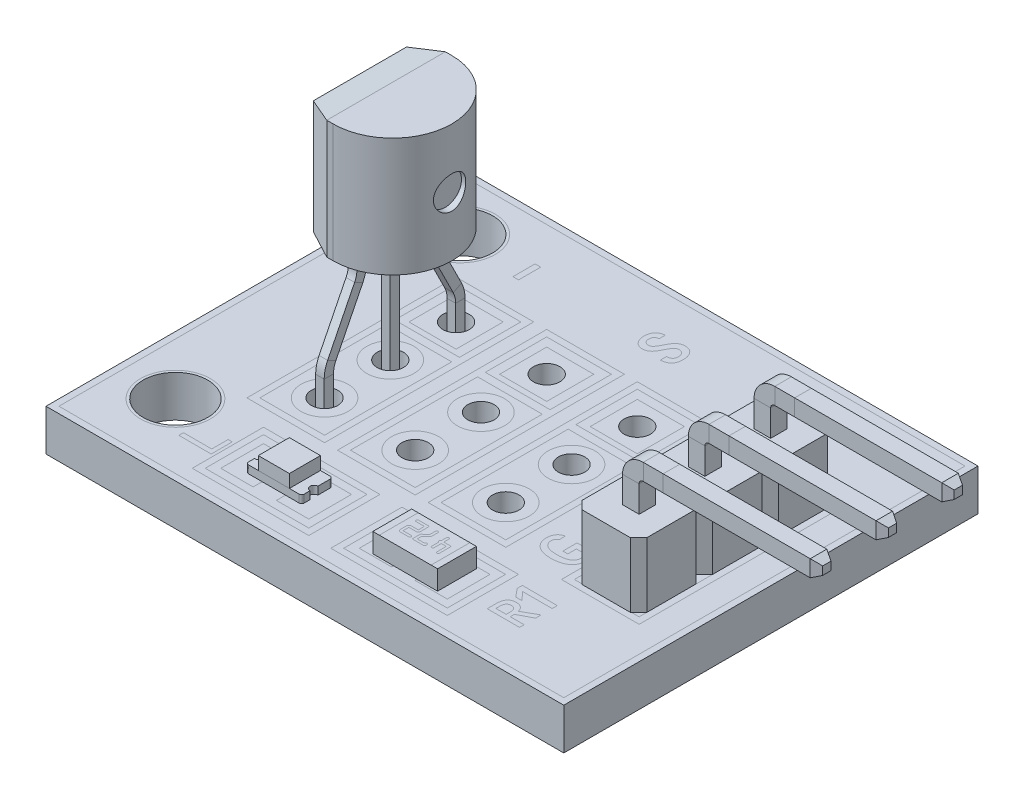
SolidWorks part; units mm, degrees
ref_plane "Front Plane" through (0, 0, 0) normal (0, 0, 1) x (1, 0, 0)
ref_plane "Top Plane" through (0, 0, 0) normal (0, 1, 0) x (1, 0, 0)
ref_plane "Right Plane" through (0, 0, 0) normal (1, 0, 0) x (0, 0, -1)
sketch "Sketch2" plane through (0, 0, 0) normal (0, 1, 0) x (1, 0, 0)
  line L0 (7.25, -2.34) -> (7.25, 2.74) construction
  line L5 (10, 8) -> (-10, 8)
  line L6 (10, 8) -> (10, -8)
  line L7 (10, -8) -> (-10, -8)
  line L8 (-10, 8) -> (-10, -8)
  circle A0 centre (-7.75, -5.25) radius 1.25
  circle A1 centre (-7.75, 5.75) radius 1.25
  circle A2 centre (2.1, 0.2) radius 0.51
  circle A3 centre (2.1, 2.74) radius 0.51
  circle A4 centre (2.1, -2.34) radius 0.51
  circle A5 centre (-1.4, -2.34) radius 0.51
  circle A6 centre (-1.4, 0.2) radius 0.51
  circle A7 centre (-1.4, 2.74) radius 0.51
  circle A8 centre (-4.9, -2.34) radius 0.51
  circle A9 centre (-4.9, 0.2) radius 0.51
  circle A10 centre (-4.9, 2.74) radius 0.51
  circle A11 centre (7.25, 0.2) radius 0.51
  circle A12 centre (7.25, 2.74) radius 0.51
  circle A13 centre (7.25, -2.34) radius 0.51
  point P35 (10, 0)
  point P37 (0, 8)
  dimension "D1" = 2.5
  dimension "D4" = 2.25
  dimension "D5" = 2.75
  dimension "D6" = 1.02
  dimension "D7" = 8.2
  dimension "D8" = 7.9
  dimension "D10" = 2.54
  dimension "D11" = 2.54
  dimension "D12" = 1.02
  dimension "D13" = 2.75
  dimension "D2" = 16
  dimension "D3" = 20
  dimension "D9" = 2.25
  dimension "D14" = 3
extrude "Boss-Extrude1" add sketch "Sketch2" along normal blind 1.6
sketch "Sketch3" plane through (0, 1.6, 0) normal (0, 1, 0) x (1, 0, 0)
  line L0 (-6.15, 3.99) -> (-3.65, 3.99)
  line L1 (-5.81, 1.83) -> (-3.99, 1.83)
  line L2 (-5.81, 1.83) -> (-5.81, 3.65)
  line L3 (-5.81, 3.65) -> (-3.99, 3.65)
  line L4 (-3.99, 1.83) -> (-3.99, 3.65)
  line L5 (-5.81, 1.83) -> (-3.99, 3.65) construction
  line L6 (-5.81, 3.65) -> (-3.99, 1.83) construction
  line L11 (-2.31, 1.83) -> (-0.49, 1.83)
  line L12 (-2.31, 1.83) -> (-2.31, 3.65)
  line L13 (1.19, 1.83) -> (3.01, 1.83)
  line L14 (1.19, 1.83) -> (1.19, 3.65)
  line L15 (1.19, 3.65) -> (3.01, 3.65)
  line L16 (3.01, 1.83) -> (3.01, 3.65)
  line L17 (1.19, 1.83) -> (3.01, 3.65) construction
  line L18 (1.19, 3.65) -> (3.01, 1.83) construction
  line L19 (-2.31, 3.65) -> (-0.49, 3.65)
  line L20 (-0.49, 1.83) -> (-0.49, 3.65)
  line L21 (-2.31, 1.83) -> (-0.49, 3.65) construction
  line L22 (-2.31, 3.65) -> (-0.49, 1.83) construction
  line L23 (0.6, -3.84) -> (3.6, -3.84)
  line L24 (0.6, -3.84) -> (0.6, 4.24)
  line L25 (0.6, 4.24) -> (3.6, 4.24)
  line L26 (3.6, -3.84) -> (3.6, 4.24)
  line L27 (2.1, 4.24) -> (2.1, -3.84) construction
  line L28 (0.6, 0.2) -> (3.6, 0.2) construction
  line L29 (-2.9, -3.84) -> (0.1, -3.84)
  line L30 (-2.9, -3.84) -> (-2.9, 4.24)
  line L31 (-2.9, 4.24) -> (0.1, 4.24)
  line L32 (0.1, -3.84) -> (0.1, 4.24)
  line L33 (-1.4, 4.24) -> (-1.4, -3.84) construction
  line L34 (-2.9, 0.2) -> (0.1, 0.2) construction
  line L35 (-6.4, -3.84) -> (-3.4, -3.84)
  line L36 (-6.4, -3.84) -> (-6.4, 4.24)
  line L37 (-6.4, 4.24) -> (-3.4, 4.24)
  line L38 (-3.4, -3.84) -> (-3.4, 4.24)
  line L39 (-4.9, 4.24) -> (-4.9, -3.84) construction
  line L40 (-6.4, 0.2) -> (-3.4, 0.2) construction
  line L41 (-3.65, -3.59) -> (-3.65, 1.32)
  line L42 (-6.15, -3.59) -> (-3.65, -3.59)
  line L43 (-6.15, -3.59) -> (-6.15, 1.32)
  line L44 (-2.65, -3.59) -> (-2.65, 1.32)
  line L45 (-2.65, 3.99) -> (-0.15, 3.99)
  line L46 (-0.15, -3.59) -> (-0.15, 1.32)
  line L47 (-2.65, -3.59) -> (-0.15, -3.59)
  line L48 (0.85, -3.59) -> (0.85, 1.32)
  line L49 (0.85, 3.99) -> (3.35, 3.99)
  line L50 (3.35, -3.59) -> (3.35, 1.32)
  line L51 (0.85, -3.59) -> (3.35, -3.59)
  line L52 (0.85, 1.47) -> (3.35, 1.47) construction
  line L53 (-0.15, 1.62) -> (-2.65, 1.62)
  line L54 (0.85, 1.32) -> (3.35, 1.32)
  line L56 (0.85, 1.62) -> (3.35, 1.62)
  line L58 (2.1, 1.62) -> (2.1, 1.32) construction
  line L59 (0.85, 1.47) -> (3.35, 1.47) construction
  line L60 (-3.65, 1.62) -> (-6.15, 1.62)
  line L61 (-0.15, 1.32) -> (-2.65, 1.32)
  line L62 (-3.65, 1.32) -> (-6.15, 1.32)
  line L63 (-6.15, 1.62) -> (-6.15, 3.99)
  line L64 (-3.65, 1.62) -> (-3.65, 3.99)
  line L65 (-6.15, -3.59) -> (-6.15, 3.99) construction
  line L66 (-2.65, 1.62) -> (-2.65, 3.99)
  line L67 (-3.65, -3.59) -> (-3.65, 3.99) construction
  line L68 (-0.15, 1.62) -> (-0.15, 3.99)
  line L69 (-2.65, -3.59) -> (-2.65, 3.99) construction
  line L70 (0.85, 1.62) -> (0.85, 3.99)
  line L71 (-0.15, -3.59) -> (-0.15, 3.99) construction
  line L72 (3.35, 1.62) -> (3.35, 3.99)
  line L73 (0.85, -3.59) -> (0.85, 3.99) construction
  line L74 (10, -8) -> (-10, -8) construction
  line L75 (3.35, -3.59) -> (3.35, 3.99) construction
  line L76 (-5.1, -4.5) -> (-0.6, -4.5)
  line L77 (-5.1, -4.5) -> (-5.1, -7.25)
  line L78 (-5.1, -7.25) -> (-0.6, -7.25)
  line L79 (-0.6, -4.5) -> (-0.6, -7.25)
  line L80 (0.25, -4.5) -> (4.75, -4.5)
  line L81 (0.25, -4.5) -> (0.25, -7.25)
  line L82 (0.25, -7.25) -> (4.75, -7.25)
  line L83 (4.75, -4.5) -> (4.75, -7.25)
  line L84 (-10, 8) -> (-10, -8) construction
  line L85 (-4.85, -4.75) -> (-0.85, -4.75)
  line L86 (-0.85, -4.75) -> (-0.85, -7)
  line L87 (-4.85, -7) -> (-0.85, -7)
  line L88 (-4.85, -4.75) -> (-4.85, -7)
  line L89 (0.5, -4.75) -> (0.5, -7)
  line L90 (0.5, -7) -> (4.5, -7)
  line L91 (4.5, -4.75) -> (4.5, -7)
  line L92 (0.5, -4.75) -> (4.5, -4.75)
  line L93 (-2.85, -7) -> (-2.85, -4.75) construction
  line L94 (-4.55, -5.05) -> (-3.3, -5.05)
  line L95 (-4.55, -5.05) -> (-4.55, -6.7)
  line L96 (-4.55, -6.7) -> (-3.3, -6.7)
  line L97 (-3.3, -5.05) -> (-3.3, -6.7)
  line L98 (-4.55, -5.05) -> (-3.3, -6.7) construction
  line L99 (-4.55, -6.7) -> (-3.3, -5.05) construction
  line L100 (-1.15, -6.7) -> (-2.4, -6.7)
  line L101 (-0.175, -4.3747) -> (-0.175, -7.1247) construction
  line L102 (-2.4, -5.05) -> (-2.4, -6.7)
  line L103 (-1.15, -5.05) -> (-2.4, -5.05)
  line L104 (-1.15, -5.05) -> (-1.15, -6.7)
  line L105 (0.8, -5.05) -> (0.8, -6.7)
  line L106 (0.8, -5.05) -> (2.05, -5.05)
  line L107 (2.05, -5.05) -> (2.05, -6.7)
  line L108 (0.8, -6.7) -> (2.05, -6.7)
  line L109 (4.2, -6.7) -> (2.95, -6.7)
  line L110 (2.95, -5.05) -> (2.95, -6.7)
  line L111 (4.2, -5.05) -> (2.95, -5.05)
  line L112 (4.2, -5.05) -> (4.2, -6.7)
  line L113 (0.75, 5.1) -> (0.75, 6.35) construction
  line L114 (2.1, -2.34) -> (7.25, -2.34) construction
  line L115 (4.675, -2.34) -> (4.675, 5.07) construction
  line L116 (6, -3.59) -> (6, 1.32)
  line L117 (8.5, -3.59) -> (6, -3.59)
  line L118 (8.5, -3.59) -> (8.5, 1.32)
  line L119 (8.5, 1.32) -> (6, 1.32)
  line L120 (6, 1.62) -> (6, 3.99)
  line L121 (8.5, 3.99) -> (6, 3.99)
  line L122 (8.5, 1.62) -> (8.5, 3.99)
  line L123 (8.5, 1.62) -> (6, 1.62)
  line L124 (8.75, 4.24) -> (5.75, 4.24)
  line L125 (5.75, -3.84) -> (5.75, 4.24)
  line L126 (8.75, -3.84) -> (5.75, -3.84)
  line L127 (8.75, -3.84) -> (8.75, 4.24)
  line L128 (10, 8) -> (-10, 8) construction
  line L129 (6.5437, -6.53) -> (6.5437, -4.33) construction
  line L130 (-5.2108, -6.7051) -> (-5.2108, -4.5051) construction
  line L131 (-5.8918, 5.1355) -> (-5.8918, 6.6) construction
  line L132 (5.6128, -3.6) -> (5.6128, 4.4) construction
  line L141 (9.75, -7.75) -> (9.75, 7.75)
  line L142 (9.75, 7.75) -> (-9.75, 7.75)
  line L143 (-9.75, 7.75) -> (-9.75, -7.75)
  line L144 (-9.75, -7.75) -> (9.75, -7.75)
  line L145 (9.75, -7.75) -> (9.75, 7.75)
  line L146 (9.75, 7.75) -> (-9.75, 7.75)
  line L147 (-9.75, 7.75) -> (-9.75, -7.75)
  line L148 (-9.75, -7.75) -> (9.75, -7.75)
  circle A0 centre (2.1, 0.2) radius 0.91
  circle A1 centre (2.1, 0.2) radius 0.51 construction
  circle A3 centre (2.1, -2.34) radius 0.91
  circle A4 centre (-1.4, -2.34) radius 0.91
  circle A5 centre (-4.9, -2.34) radius 0.91
  circle A6 centre (-4.9, 0.2) radius 0.91
  circle A9 centre (-1.4, 0.2) radius 0.91
  circle A10 centre (7.25, 0.2) radius 0.81
  circle A11 centre (7.25, 2.74) radius 0.81
  circle A12 centre (7.25, -2.34) radius 0.81
  circle A13 centre (7.25, 0.2) radius 0.51 construction
  circle A14 centre (-7.75, 5.75) radius 1.35
  circle A15 centre (-7.75, 5.75) radius 1.25 construction
  circle A16 centre (-7.75, -5.25) radius 1.35
  circle A17 centre (-7.75, -5.25) radius 1.25 construction
  text T0 "S" font "OCR-B 10 BT" height 1.5
  text T1 "R1" font "OCR-B 10 BT" height 1.25
  text T4 "L" font "OCR-B 10 BT" height 1.25
  text T5 "-" font "OCR-B 10 BT" height 1.25
  text T6 "GRY" font "OCR-B 10 BT" height 1.5
  point P5 (-4.9, 2.74)
  point P18 (-1.4, 2.74)
  point P41 (2.1, 2.74)
  point P80 (2.1, 1.47)
  point P104 (-3.925, -5.875)
  dimension "D1" = 0.4
  dimension "D2" = 0.3
  dimension "D3" = 0.1
  dimension "D4" = 0.1
  dimension "D5" = 3
  dimension "D6" = 8.08
  dimension "D8" = 0.36
  dimension "D9" = 0.3
  dimension "D10" = 2.37
  dimension "D11" = 2.75
  dimension "D12" = 4.5
  dimension "D13" = 0.75
  dimension "D14" = 0.85
  dimension "D15" = 4.9
  dimension "D17" = 1.25
  dimension "D18" = 0.3
  dimension "D19" = 0.3
  dimension "D20" = 0.3
  dimension "D21" = 0.425
  dimension "D22" = 1.25
  dimension "D23" = 1.4
  dimension "D24" = 2.2
  dimension "D25" = 1.47
  dimension "D26" = 2.2
  dimension "D27" = 1.4645
  dimension "D28" = 1.4
  dimension "D29" = 8
  dimension "D30" = 4.4
  dimension "D32" = 9
  dimension "D7" = 0.25
  dimension "D16" = 0.25
  dimension "D31" = 0.25
sketch "Sketch4" plane through (0, 0, 0) normal (0, -1, 0) x (1, 0, 0)
  line L0 (-5.81, -1.83) -> (-5.81, -3.65) construction
  line L1 (-5.81, -3.65) -> (-3.99, -3.65) construction
  line L2 (-3.99, -1.83) -> (-3.99, -3.65) construction
  line L3 (-5.81, -1.83) -> (-3.99, -1.83) construction
  line L4 (-2.31, -1.83) -> (-0.49, -1.83) construction
  line L5 (-2.31, -1.83) -> (-2.31, -3.65) construction
  line L6 (-2.31, -3.65) -> (-0.49, -3.65) construction
  line L7 (-0.49, -1.83) -> (-0.49, -3.65) construction
  line L8 (1.19, -1.83) -> (3.01, -1.83) construction
  line L9 (3.01, -1.83) -> (3.01, -3.65) construction
  line L10 (1.19, -3.65) -> (3.01, -3.65) construction
  line L11 (1.19, -1.83) -> (1.19, -3.65) construction
  line L12 (-5.81, -1.83) -> (-5.81, -3.65)
  line L13 (-5.81, -3.65) -> (-3.99, -3.65)
  line L14 (-3.99, -1.83) -> (-3.99, -3.65)
  line L15 (-5.81, -1.83) -> (-3.99, -1.83)
  line L16 (-2.31, -1.83) -> (-0.49, -1.83)
  line L17 (-2.31, -1.83) -> (-2.31, -3.65)
  line L18 (-2.31, -3.65) -> (-0.49, -3.65)
  line L19 (-0.49, -1.83) -> (-0.49, -3.65)
  line L20 (1.19, -1.83) -> (3.01, -1.83)
  line L21 (3.01, -1.83) -> (3.01, -3.65)
  line L22 (1.19, -3.65) -> (3.01, -3.65)
  line L23 (1.19, -1.83) -> (1.19, -3.65)
  line L32 (9.75, -7.75) -> (9.75, 7.75)
  line L33 (9.75, 7.75) -> (-9.75, 7.75)
  line L34 (-9.75, 7.75) -> (-9.75, -7.75)
  line L35 (-9.75, -7.75) -> (9.75, -7.75)
  line L36 (9.75, -7.75) -> (9.75, 7.75)
  line L37 (9.75, 7.75) -> (-9.75, 7.75)
  line L38 (-9.75, 7.75) -> (-9.75, -7.75)
  line L39 (-9.75, -7.75) -> (9.75, -7.75)
  circle A0 centre (-7.75, 5.25) radius 1.35 construction
  circle A1 centre (-7.75, -5.75) radius 1.35 construction
  circle A2 centre (-4.9, -0.2) radius 0.91 construction
  circle A3 centre (-4.9, 2.34) radius 0.91 construction
  circle A4 centre (-1.4, 2.34) radius 0.91 construction
  circle A5 centre (-1.4, -0.2) radius 0.91 construction
  circle A6 centre (2.1, -0.2) radius 0.91 construction
  circle A7 centre (2.1, 2.34) radius 0.91 construction
  circle A8 centre (7.25, 2.34) radius 0.81 construction
  circle A9 centre (7.25, -0.2) radius 0.81 construction
  circle A10 centre (7.25, -2.74) radius 0.81 construction
  circle A11 centre (-7.75, 5.25) radius 1.35
  circle A12 centre (-7.75, -5.75) radius 1.35
  circle A13 centre (-4.9, -0.2) radius 0.91
  circle A14 centre (-4.9, 2.34) radius 0.91
  circle A15 centre (-1.4, 2.34) radius 0.91
  circle A16 centre (-1.4, -0.2) radius 0.91
  circle A17 centre (2.1, -0.2) radius 0.91
  circle A18 centre (2.1, 2.34) radius 0.91
  circle A19 centre (7.25, 2.34) radius 0.81
  circle A20 centre (7.25, -0.2) radius 0.81
  circle A21 centre (7.25, -2.74) radius 0.81
  dimension "D1" = 0.25
split line "Split Line1"
split line "Split Line2"
sketch "Sketch6" plane through (0, 1.6, 0) normal (0, 1, 0) x (1, 0, 0)
  line L0 (4.2, -5.875) -> (0.8, -5.875) construction
  line L5 (4.2, -6.7) -> (4.2, -5.05) construction
  line L6 (0.8, -5.05) -> (0.8, -6.7) construction
  line L8 (3.75, -5.125) -> (1.25, -5.125)
  line L9 (3.75, -5.125) -> (3.75, -6.625)
  line L10 (3.75, -6.625) -> (1.25, -6.625)
  line L11 (1.25, -5.125) -> (1.25, -6.625)
  line L12 (3.75, -5.125) -> (1.25, -6.625) construction
  line L13 (3.75, -6.625) -> (1.25, -5.125) construction
  point P6 (2.5, -5.875)
  dimension "D1" = 1.5
  dimension "D2" = 2.5
extrude "Boss-Extrude2" add sketch "Sketch6" along normal blind 0.75
sketch "Sketch7" plane through (0, 2.35, 0) normal (0, 1, 0) x (1, 0, 0)
  line L0 (1.25, -6.625) -> (3.75, -6.625) construction
  line L1 (3.5, -6.625) -> (1.5, -6.625)
  line L2 (3.5, -6.625) -> (3.5, -5.125)
  line L3 (3.5, -5.125) -> (1.5, -5.125)
  line L4 (1.5, -6.625) -> (1.5, -5.125)
  line L5 (3.75, -5.125) -> (1.25, -5.125) construction
  line L6 (2.5, -6.625) -> (2.5, -5.125) construction
  line L7 (3.5, -5.3646) -> (1.5, -5.3646) construction
  text T0 "472" font "OCR A Extended" height 0.75
  point P9 (2.5, -6.625)
  point P16 (2.5, -5.3646)
  dimension "D1" = 2
split line "Split Line3"
sketch "Sketch8" plane through (0, 1.6, 0) normal (0, 1, 0) x (1, 0, 0)
  line L0 (-1.15, -5.875) -> (-4.55, -5.875) construction
  line L1 (-1.15, -6.7) -> (-1.15, -5.05) construction
  line L2 (-4.55, -5.05) -> (-4.55, -6.7) construction
  line L3 (-2.85, -6.5747) -> (-2.85, -5.1753) construction
  line L4 (-3.3, -5.05) -> (-4.55, -5.05) construction
  line L5 (-1.875, -6.3497) -> (-3.825, -6.3497)
  line L6 (-1.775, -6.2497) -> (-1.775, -6.025)
  line L7 (-1.875, -5.1497) -> (-3.825, -5.1497)
  line L8 (-3.925, -6.2497) -> (-3.925, -6.025)
  line L9 (-1.15, -5.05) -> (-2.4, -5.05) construction
  line L10 (-1.775, -5.725) -> (-1.775, -5.2497)
  line L11 (-3.925, -5.725) -> (-3.925, -5.2497)
  arc A0 (-1.775, -5.725) -> (-1.775, -6.025) centre (-1.775, -5.875) ccw
  arc A1 (-3.925, -6.025) -> (-3.925, -5.725) centre (-3.925, -5.875) ccw
  arc A2 (-3.825, -6.3497) -> (-3.925, -6.2497) centre (-3.825, -6.2497) cw
  arc A3 (-3.825, -5.1497) -> (-3.925, -5.2497) centre (-3.825, -5.2497) ccw
  arc A4 (-1.775, -5.2497) -> (-1.875, -5.1497) centre (-1.875, -5.2497) ccw
  arc A5 (-1.875, -6.3497) -> (-1.775, -6.2497) centre (-1.875, -6.2497) ccw
  point P9 (-2.85, -5.875)
  point P15 (-3.925, -5.05)
  point P18 (-1.775, -5.05)
  dimension "D2" = 0.3
  dimension "D3" = 0.1
  dimension "D1" = 1.2
extrude "Boss-Extrude3" add sketch "Sketch8" along normal blind 0.3
sketch "Sketch9" plane through (0, 1.9, 0) normal (0, 1, 0) x (1, 0, 0)
  line L0 (-3.825, -6.3497) -> (-1.875, -6.3497) construction
  line L1 (-2.25, -6.3497) -> (-3.45, -6.3497)
  line L2 (-2.25, -6.3497) -> (-2.25, -5.1497)
  line L3 (-2.25, -5.1497) -> (-3.45, -5.1497)
  line L4 (-3.45, -6.3497) -> (-3.45, -5.1497)
  line L5 (-3.3, -6.3497) -> (-2.4, -6.3497) construction
  line L6 (-1.875, -5.1497) -> (-3.825, -5.1497) construction
  point P16 (-2.85, -6.3497)
  point P17 (-2.85, -6.3497)
extrude "Boss-Extrude4" add sketch "Sketch9" along normal blind 0.5
sketch "Sketch10" plane through (0, 0, 5.1497) normal (0, 0, -1) x (-1, 0, 0)
  line L0 (2.25, 1.9) -> (3.45, 1.9)
split line "Split Line4"
sketch "Sketch11" plane through (0, 1.6, 0) normal (0, 1, 0) x (1, 0, 0)
  line L0 (6.32, 1.47) -> (6, 1.79)
  line L1 (8.18, 1.47) -> (6.32, 1.47)
  line L2 (8.5, 1.79) -> (8.5, 3.69)
  line L3 (8.18, 4.01) -> (6.32, 4.01)
  line L4 (6, 1.79) -> (6, 3.69)
  line L5 (8.5, 1.47) -> (6, 4.01) construction
  line L6 (8.5, 4.01) -> (6, 1.47) construction
  line L7 (8.5, 1.79) -> (8.18, 1.47)
  line L8 (8.5, 3.69) -> (8.18, 4.01)
  line L9 (6.32, 4.01) -> (6, 3.69)
  line L10 (8.18, -1.07) -> (6.32, -1.07)
  line L11 (6.32, -1.07) -> (6, -0.75)
  line L12 (6, -0.75) -> (6, 1.15)
  line L13 (6.32, 1.47) -> (6, 1.15)
  line L14 (8.18, 1.47) -> (6.32, 1.47)
  line L15 (8.5, 1.15) -> (8.18, 1.47)
  line L16 (8.5, -0.75) -> (8.5, 1.15)
  line L17 (8.5, -0.75) -> (8.18, -1.07)
  line L18 (8.18, -3.61) -> (6.32, -3.61)
  line L19 (6.32, -3.61) -> (6, -3.29)
  line L20 (6, -3.29) -> (6, -1.39)
  line L21 (6.32, -1.07) -> (6, -1.39)
  line L22 (8.18, -1.07) -> (6.32, -1.07)
  line L23 (8.5, -1.39) -> (8.18, -1.07)
  line L24 (8.5, -3.29) -> (8.5, -1.39)
  line L25 (8.5, -3.29) -> (8.18, -3.61)
  point P0 (7.25, 2.74)
  dimension "D1" = 2.5
  dimension "D2" = 2.54
  dimension "D3" = 0.32
  dimension "D4" = 45
  dimension "D5" = 0.32
  dimension "D6" = 45
  dimension "D7" = 0.32
  dimension "D8" = 45
  dimension "D9" = 0.32
  dimension "D10" = 45
  dimension "D11" = 3
extrude "Boss-Extrude5" add sketch "Sketch11" along normal blind 2.5 contours L25 L24 L23 L10 L21 L20 L19 L18 | L17 L16 L15 L1 L13 L12 L11 L10 | L3 L9 L4 L0 L1 L7 L2 L8
sketch "Sketch12" plane through (0, 1.6, 0) normal (0, -1, 0) x (1, 0, 0)
  line L0 (7.57, 0.12) -> (7.57, -0.52)
  line L1 (6.93, -2.42) -> (7.57, -2.42)
  line L2 (6.93, -2.42) -> (6.93, -3.06)
  line L3 (6.93, -3.06) -> (7.57, -3.06)
  line L4 (7.57, -2.42) -> (7.57, -3.06)
  line L5 (6.93, -2.42) -> (7.57, -3.06) construction
  line L6 (6.93, -3.06) -> (7.57, -2.42) construction
  line L7 (6.93, 0.12) -> (7.57, 0.12)
  line L8 (6.93, 0.12) -> (6.93, -0.52)
  line L9 (6.93, -0.52) -> (7.57, -0.52)
  line L10 (7.57, 2.66) -> (7.57, 2.02)
  line L11 (6.93, 2.66) -> (7.57, 2.66)
  line L12 (6.93, 2.66) -> (6.93, 2.02)
  line L13 (6.93, 2.02) -> (7.57, 2.02)
  point P0 (7.25, -2.74)
  dimension "D1" = 0.64
  dimension "D2" = 3
extrude "Boss-Extrude6" add sketch "Sketch12" along normal blind 2.68
sketch "Sketch13" plane through (0, -1.08, 0) normal (0, -1, 0) x (1, 0, 0)
  line L0 (6.93, 2.02) -> (7.57, 2.02) construction
  line L1 (7.57, 2.02) -> (7.57, 2.66) construction
  line L2 (7.57, 2.66) -> (6.93, 2.66) construction
  line L3 (6.93, 2.66) -> (6.93, 2.02) construction
  line L4 (7.57, -3.06) -> (7.57, -2.42)
  line L5 (7.57, -2.42) -> (6.93, -2.42)
  line L6 (6.93, -2.42) -> (6.93, -3.06)
  line L7 (6.93, -3.06) -> (7.57, -3.06)
  line L8 (7.57, -3.06) -> (7.57, -2.42)
  line L9 (7.57, -2.42) -> (6.93, -2.42)
  line L10 (6.93, -2.42) -> (6.93, -3.06)
  line L11 (6.93, -3.06) -> (7.57, -3.06)
  line L12 (6.93, -0.52) -> (7.57, -0.52) construction
  line L13 (7.57, -0.52) -> (7.57, 0.12) construction
  line L14 (7.57, 0.12) -> (6.93, 0.12) construction
  line L15 (6.93, 0.12) -> (6.93, -0.52) construction
  line L16 (6.93, 2.02) -> (7.57, 2.02)
  line L17 (7.57, 2.02) -> (7.57, 2.66)
  line L18 (7.57, 2.66) -> (6.93, 2.66)
  line L19 (6.93, 2.66) -> (6.93, 2.02)
  line L20 (6.93, -0.52) -> (7.57, -0.52)
  line L21 (7.57, -0.52) -> (7.57, 0.12)
  line L22 (7.57, 0.12) -> (6.93, 0.12)
  line L23 (6.93, 0.12) -> (6.93, -0.52)
  dimension "D1" = 0
extrude "Boss-Extrude7" add sketch "Sketch13" along normal blind 0.32 draft 26.7
sketch "Sketch14" plane through (0, 4.1, 0) normal (0, 1, 0) x (1, 0, 0)
  line L4 (7.57, -2.66) -> (7.57, -2.02)
  line L5 (7.57, -2.02) -> (6.93, -2.02)
  line L6 (6.93, -2.02) -> (6.93, -2.66)
  line L7 (6.93, -2.66) -> (7.57, -2.66)
  line L8 (7.57, -2.66) -> (7.57, -2.02)
  line L9 (7.57, -2.02) -> (6.93, -2.02)
  line L10 (6.93, -2.02) -> (6.93, -2.66)
  line L11 (6.93, -2.66) -> (7.57, -2.66)
  line L12 (6.93, 2.42) -> (7.57, 2.42)
  line L13 (7.57, 2.42) -> (7.57, 3.06)
  line L14 (7.57, 3.06) -> (6.93, 3.06)
  line L15 (6.93, 3.06) -> (6.93, 2.42)
  line L16 (6.93, 2.42) -> (7.57, 2.42)
  line L17 (7.57, 2.42) -> (7.57, 3.06)
  line L18 (7.57, 3.06) -> (6.93, 3.06)
  line L19 (6.93, 3.06) -> (6.93, 2.42)
  line L20 (7.57, -0.12) -> (7.57, 0.52)
  line L21 (7.57, 0.52) -> (6.93, 0.52)
  line L22 (6.93, 0.52) -> (6.93, -0.12)
  line L23 (6.93, -0.12) -> (7.57, -0.12)
  line L24 (7.57, -0.12) -> (7.57, 0.52)
  line L25 (7.57, 0.52) -> (6.93, 0.52)
  line L26 (6.93, 0.52) -> (6.93, -0.12)
  line L27 (6.93, -0.12) -> (7.57, -0.12)
  dimension "D1" = 0
  dimension "D2" = 0
  dimension "D3" = 0
sketch3d "3DSketch1"
  line L3 (7.57, 4.1, -2.74) -> (6.93, 4.1, -2.74) construction
  line L4 (7.57, 4.1, -2.42) -> (7.57, 4.1, -3.06) construction
  line L5 (6.93, 4.1, -3.06) -> (6.93, 4.1, -2.42) construction
  line L8 (7.25, 4.1, -2.74) -> (7.25, 5.12, -2.74)
  line L9 (7.73, 5.6, -2.74) -> (8.5, 5.6, -2.74)
  line L10 (8.5, 5.6, -2.74) -> (14.18, 5.6, -2.74)
  line L11 (8.5, 4.1, -1.79) -> (8.5, 4.1, -3.69) construction
  line L12 (8.5, 4.1, -2.74) -> (8.5, 5.6, -2.74) construction
  arc A0 (7.25, 5.12, -2.74) -> (7.73, 5.6, -2.74) centre (7.73, 5.12, -2.74) ccw
  point P15 (7.25, 5.6, -2.74)
  point P16 (7.73, 5.12, -3.22)
  dimension "D3" = 0.48
  dimension "D1" = 1.5
  dimension "D2" = 5.68
sweep "Sweep1" add profiles "Sketch14" path "3DSketch1"
sketch "Sketch15" plane through (14.18, 0, 0) normal (1, 0, 0) x (0, 0, -1)
  line L0 (-2.66, 5.92) -> (-2.66, 5.28) construction
  line L1 (-2.66, 5.28) -> (-2.02, 5.28) construction
  line L2 (-2.02, 5.28) -> (-2.02, 5.92) construction
  line L3 (-2.02, 5.92) -> (-2.66, 5.92) construction
  line L4 (-0.12, 5.92) -> (-0.12, 5.28) construction
  line L5 (-0.12, 5.28) -> (0.52, 5.28) construction
  line L6 (0.52, 5.28) -> (0.52, 5.92) construction
  line L7 (0.52, 5.92) -> (-0.12, 5.92) construction
  line L8 (3.06, 5.92) -> (2.42, 5.92) construction
  line L9 (2.42, 5.92) -> (2.42, 5.28) construction
  line L10 (2.42, 5.28) -> (3.06, 5.28) construction
  line L11 (3.06, 5.28) -> (3.06, 5.92) construction
  line L12 (-2.66, 5.92) -> (-2.66, 5.28)
  line L13 (-2.66, 5.28) -> (-2.02, 5.28)
  line L14 (-2.02, 5.28) -> (-2.02, 5.92)
  line L15 (-2.02, 5.92) -> (-2.66, 5.92)
  line L16 (-0.12, 5.92) -> (-0.12, 5.28)
  line L17 (-0.12, 5.28) -> (0.52, 5.28)
  line L18 (0.52, 5.28) -> (0.52, 5.92)
  line L19 (0.52, 5.92) -> (-0.12, 5.92)
  line L20 (3.06, 5.92) -> (2.42, 5.92)
  line L21 (2.42, 5.92) -> (2.42, 5.28)
  line L22 (2.42, 5.28) -> (3.06, 5.28)
  line L23 (3.06, 5.28) -> (3.06, 5.92)
extrude "Boss-Extrude8" add sketch "Sketch15" along normal blind 0.32 draft 26.7
ref_plane "Plane3" through (0, 6.1, 0) normal (0, 1, 0) x (1, 0, 0)
sketch "Sketch16" plane through (0, 6.1, 0) normal (0, 1, 0) x (1, 0, 0)
  line L0 (-4.815, -2.09) -> (-4.815, 2.49) construction
  line L4 (-4.815, -2.09) -> (-5.065, -2.09)
  line L5 (-5.065, -2.09) -> (-5.065, 2.49)
  line L6 (-5.065, 2.49) -> (-4.815, 2.49)
  arc A1 (-4.815, -2.09) -> (-4.815, 2.49) centre (-4.815, 0.2) ccw
  point P2 (-5.065, 0.2)
  point P7 (-4.9, 0.2)
  point P9 (-4.815, 0.2)
  dimension "D1" = 2.29
  dimension "D2" = 0.25
  dimension "D3" = 0.165
extrude "Boss-Extrude9" add sketch "Sketch16" along normal blind 4.58 separate body
sketch "Sketch20" plane through (0, 6.1, 0) normal (0, -1, 0) x (1, 0, 0)
  line L0 (-5.065, -1.47) -> (-5.065, 1.07) construction
  line L3 (-5.065, -2.49) -> (-5.065, 2.09) construction
  point P0 (-5.065, -0.2)
  point P5 (-5.065, -0.2)
  dimension "D1" = 2.54
ref_plane "Plane1" through (-6.075, 0, 0) normal (1, 0, 0) x (0, 0, -1)
ref_plane "Plane2" through (-2.525, 0, 0) normal (-1, 0, 0) x (0, 0, 1)
sketch "Sketch17" plane through (-6.075, 0, 0) normal (1, 0, 0) x (0, 0, -1)
  line L1 (2, 10.58) -> (-1.6, 10.58)
  line L2 (2, 10.58) -> (2, 6.2)
  line L3 (2, 6.2) -> (-1.6, 6.2)
  line L4 (-1.6, 10.58) -> (-1.6, 6.2)
  line L7 (2.49, 10.68) -> (-2.09, 10.68) construction
  line L8 (-2.09, 10.68) -> (-2.09, 6.1) construction
  point P5 (-2.09, 8.39)
  point P8 (0.2, 6.2)
  point P10 (0.2, 10.68)
  point P11 (-1.6, 8.39)
  dimension "D1" = 4.38
  dimension "D2" = 3.6
loft "Loft1" add profiles "Sketch17" section face at (-5.065, 8.39, -0.2) section "Sketch17"
sketch "Sketch21" plane through (-6.075, 0, 0) normal (-1, 0, 0) x (0, 0, 1)
  line L0 (-2, 9.58) -> (1.6, 9.58) construction
  line L1 (-2, 6.2) -> (-2, 10.58) construction
  line L2 (1.6, 10.58) -> (1.6, 6.2) construction
  line L3 (-2, 8.58) -> (1.6, 8.58) construction
  line L4 (-2, 10.58) -> (1.6, 10.58) construction
  text T0 "DALLAS" font "Century Gothic" height 0.65
  text T1 "18B20" font "Century Gothic" height 0.65
  dimension "D2" = 1
  dimension "D1" = 1
split line "Split Line5"
sketch "Sketch22" plane through (-2.525, 0, 0) normal (-1, 0, 0) x (0, 0, 1)
  line L0 (-0.2, 10.68) -> (-0.2, 6.1) construction
  line L1 (2.09, 10.68) -> (-2.49, 10.68) construction
  line L2 (-2.49, 6.1) -> (2.09, 6.1) construction
  circle A0 centre (-0.2, 8.39) radius 0.625
  dimension "D1" = 1.25
extrude "Cut-Extrude3" cut sketch "Sketch22" along normal blind 0.25
sketch "Sketch19" plane through (0, 6.1, 0) normal (0, -1, 0) x (1, 0, 0)
  line L1 (-5.065, -0.38) -> (-4.735, -0.38)
  line L2 (-5.065, -0.38) -> (-5.065, -0.02)
  line L3 (-5.065, -0.02) -> (-4.735, -0.02)
  line L4 (-4.735, -0.38) -> (-4.735, -0.02)
  line L5 (-5.065, -0.38) -> (-4.735, -0.02) construction
  line L6 (-5.065, -0.02) -> (-4.735, -0.38) construction
  line L7 (-5.065, -1.47) -> (-5.065, 1.07) construction
  point P0 (-4.9, -0.2)
  point P6 (-5.065, -0.2)
  point P11 (-5.065, -0.2)
  dimension "D1" = 0.33
  dimension "D2" = 0.36
extrude "Boss-Extrude11" add sketch "Sketch19" along normal blind 7
sketch3d "3DSketch2"
  line L0 (-5.065, 6.1, 1.07) -> (-5.065, 5.45, 1.07)
  line L1 (-5.065, 6.1, -1.47) -> (-5.065, 6.1, 1.07) construction
  line L2 (-5.065, 4.9676, 1.1837) -> (-5.065, 2.8793, 2.2263)
  line L3 (-5.065, 2.3968, 2.34) -> (-5.065, -0.6032, 2.34)
  line L5 (-5.065, 6.1, -0.02) -> (-5.065, 6.1, 2.09) construction
  line L6 (-4.9, 1.6, 2.34) -> (-5.065, 1.6, 2.34) construction
  line L7 (-4.9, 1.6, 2.34) -> (-4.9, 0, 2.34) construction
  arc A0 (-5.065, 2.8793, 2.2263) -> (-5.065, 2.3968, 2.34) centre (-5.065, 2.3968, 1.2599) ccw
  arc A1 (-5.065, 5.45, 1.07) -> (-5.065, 4.9676, 1.1837) centre (-5.065, 5.45, 2.1501) ccw
  point P12 (-5.065, 2.6514, 2.34)
  point P13 (-3.9849, 2.3968, 1.2599)
  point P16 (-5.065, 5.1954, 1.07)
  point P17 (-6.1451, 5.45, 2.1501)
  dimension "D3" = 0.165
  dimension "D1" = 3
  dimension "D2" = 0.65
ref_plane "Plane4" through (0, 0, -0.2) normal (0, 0, -1) x (-1, 0, 0)
sketch "Sketch23" plane through (0, 6.1, 0) normal (0, -1, 0) x (1, 0, 0)
  line L0 (-5.065, -0.02) -> (-5.065, 2.09) construction
  line L1 (-5.065, 0.89) -> (-4.735, 0.89)
  line L2 (-5.065, 0.89) -> (-5.065, 1.25)
  line L3 (-5.065, 1.25) -> (-4.735, 1.25)
  line L4 (-4.735, 0.89) -> (-4.735, 1.25)
  point P6 (-5.065, 1.07)
  dimension "D1" = 0.33
  dimension "D2" = 0.36
sweep "Sweep2" add profiles "Sketch23" path "3DSketch2"
mirror "Mirror1" about plane through (0, 0, -0.2) normal (0, 0, -1) of "Sweep2"
